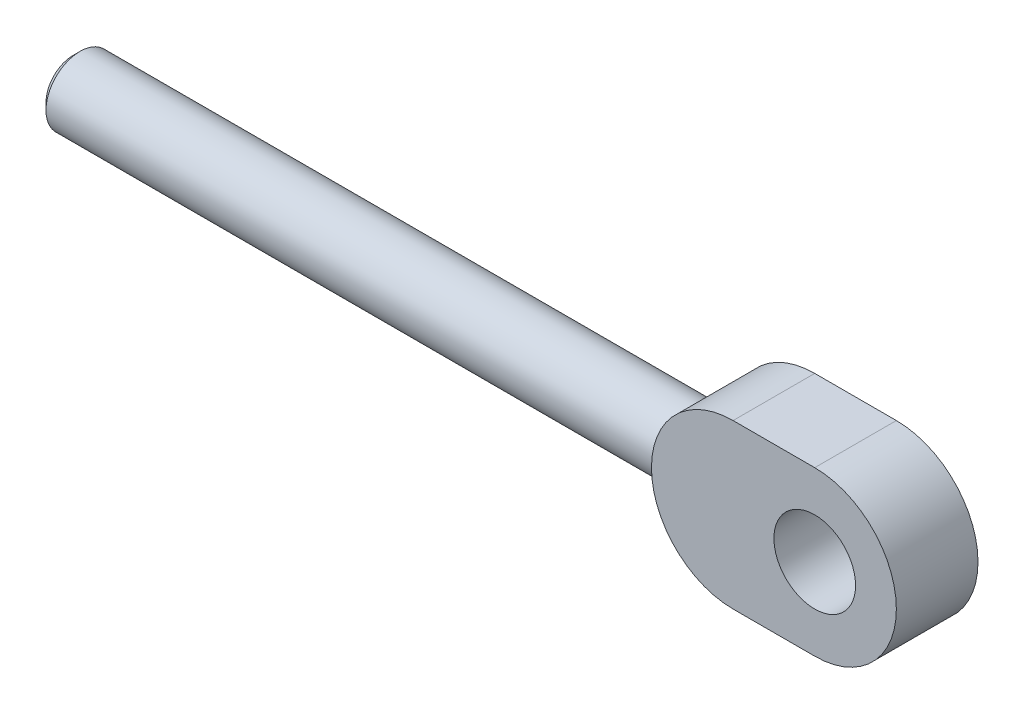
SolidWorks part; units mm, degrees
ref_plane "Piano frontale" through (0, 0, 0) normal (0, 0, 1) x (1, 0, 0)
ref_plane "Piano superiore" through (0, 0, 0) normal (0, 1, 0) x (1, 0, 0)
ref_plane "Piano destro" through (0, 0, 0) normal (1, 0, 0) x (0, 0, -1)
sketch "Schizzo1" plane through (0, 0, 0) normal (0, 0, 1) x (1, 0, 0)
  line L0 (-6, 0) -> (6, 0) construction
  line L1 (-6, 12) -> (6, 12)
  line L2 (-6, -12) -> (6, -12)
  arc A0 (-6, 12) -> (-6, -12) centre (-6, 0) ccw
  arc A1 (6, -12) -> (6, 12) centre (6, 0) ccw
  circle A2 centre (6, 0) radius 6
  point P3 (0, 0)
  dimension "D3" = 12
  dimension "D1" = 12
  dimension "D2" = 24
extrude "Estrusione-Estrusione1" add sketch "Schizzo1" along normal blind 12
ref_plane "Piano1" through (-109, 0, 0) normal (1, 0, 0) x (0, 0, -1)
sketch "Schizzo2" plane through (-109, 0, 0) normal (1, 0, 0) x (0, 0, -1)
  line L0 (-6, 12) -> (-6, -12) construction
  line L1 (-12, 12) -> (0, 12) construction
  line L2 (-12, 0) -> (0, 0) construction
  line L3 (-12, 12) -> (-12, -12) construction
  circle A0 centre (-6, 0) radius 5
  point P11 (-6, -0.4549)
  point P12 (0, 0)
  dimension "D1" = 10
extrude "Estrusione-Estrusione2" add sketch "Schizzo2" along normal up to surface (91 mm away)
chamfer "Smusso1" distance 1 angle 45 1 edges at (-109, 0, 1)
